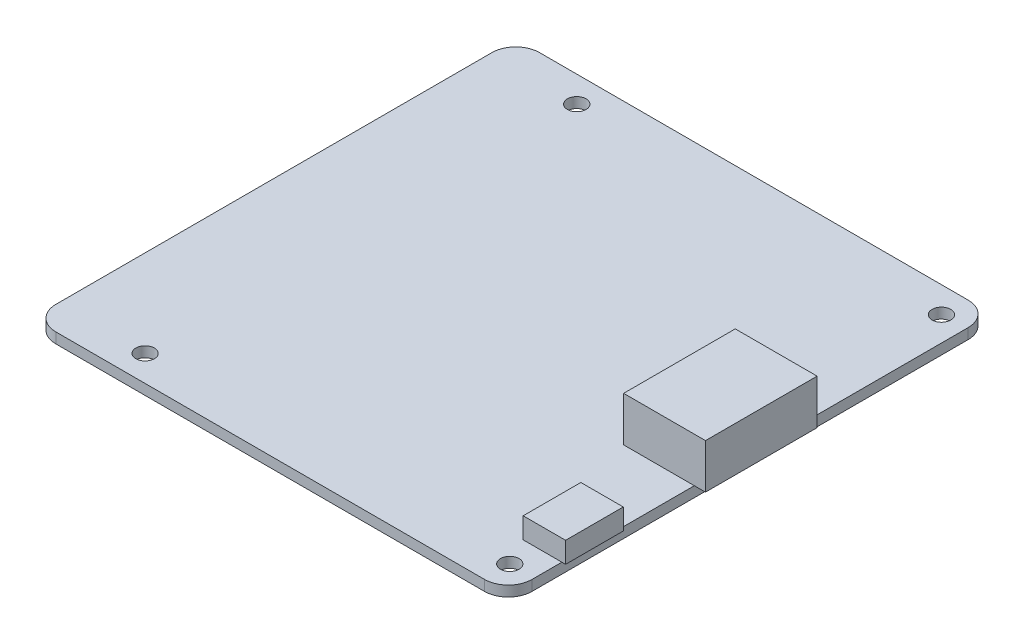
SolidWorks part; units mm, degrees
ref_plane "Front" through (0, 0, 0) normal (0, 0, 1) x (1, 0, 0)
ref_plane "Top" through (0, 0, 0) normal (0, 1, 0) x (1, 0, 0)
ref_plane "Right" through (0, 0, 0) normal (1, 0, 0) x (0, 0, -1)
sketch "Sketch1" plane through (0, 0, 0) normal (0, 1, 0) x (1, 0, 0)
  line L0 (-20.3, 29) -> (28.7, 29) construction
  line L1 (-32, -32.5) -> (32, -32.5)
  line L2 (-32, -32.5) -> (-32, 32.5)
  line L3 (-32, 32.5) -> (32, 32.5)
  line L4 (32, -32.5) -> (32, 32.5)
  line L5 (-32, -32.5) -> (32, 32.5) construction
  line L6 (-32, 32.5) -> (32, -32.5) construction
  line L10 (-20.3, 29) -> (-20.3, -29) construction
  line L11 (28.7, 29) -> (28.7, -29) construction
  line L12 (28.7, -29) -> (-20.3, -29) construction
  circle A0 centre (28.7, -29) radius 1.25
  circle A1 centre (-20.3, -29) radius 1.25
  circle A2 centre (-20.3, 29) radius 1.25
  circle A4 centre (28.7, 29) radius 1.25
  point P0 (0, 0)
  point P6 (0, 0)
  point P15 (28.7, 0)
  point P16 (32, 0)
  dimension "D3" = 2.5
  dimension "D1" = 64
  dimension "D2" = 65
  dimension "D4" = 3.3
  dimension "D5" = 58
  dimension "D6" = 49
extrude "Boss-Extrude1" add sketch "Sketch1" along normal blind 1.4
sketch "Sketch2" plane through (0, 1.4, 0) normal (0, 1, 0) x (1, 0, 0)
  line L1 (33.5, 7.5) -> (22.5, 7.5)
  line L2 (33.5, 7.5) -> (33.5, -7.5)
  line L3 (33.5, -7.5) -> (22.5, -7.5)
  line L4 (22.5, 7.5) -> (22.5, -7.5)
  line L5 (32, -32.5) -> (32, 32.5) construction
  point P6 (22.5, 0)
  dimension "D1" = 15
  dimension "D2" = 11
  dimension "D3" = 1.5
extrude "Boss-Extrude2" add sketch "Sketch2" along normal blind 6
sketch "Sketch3" plane through (0, 1.4, 0) normal (0, 1, 0) x (1, 0, 0)
  line L0 (32, -32.5) -> (32, -7.5) construction
  line L1 (32.5, -17.55) -> (26.8, -17.55)
  line L2 (32.5, -17.55) -> (32.5, -25.3)
  line L3 (32.5, -25.3) -> (26.8, -25.3)
  line L4 (26.8, -17.55) -> (26.8, -25.3)
  line L5 (-32, -32.5) -> (32, -32.5) construction
  dimension "D1" = 5.7
  dimension "D2" = 7.75
  dimension "D3" = 0.5
  dimension "D4" = 7.2
extrude "Boss-Extrude3" add sketch "Sketch3" along normal blind 2.8
fillet "Fillet1" radius 3.2 4 edges at (-32, 0.7, -32.5) (32, 0.7, -32.5) (32, 0.7, 32.5) (-32, 0.7, 32.5)
